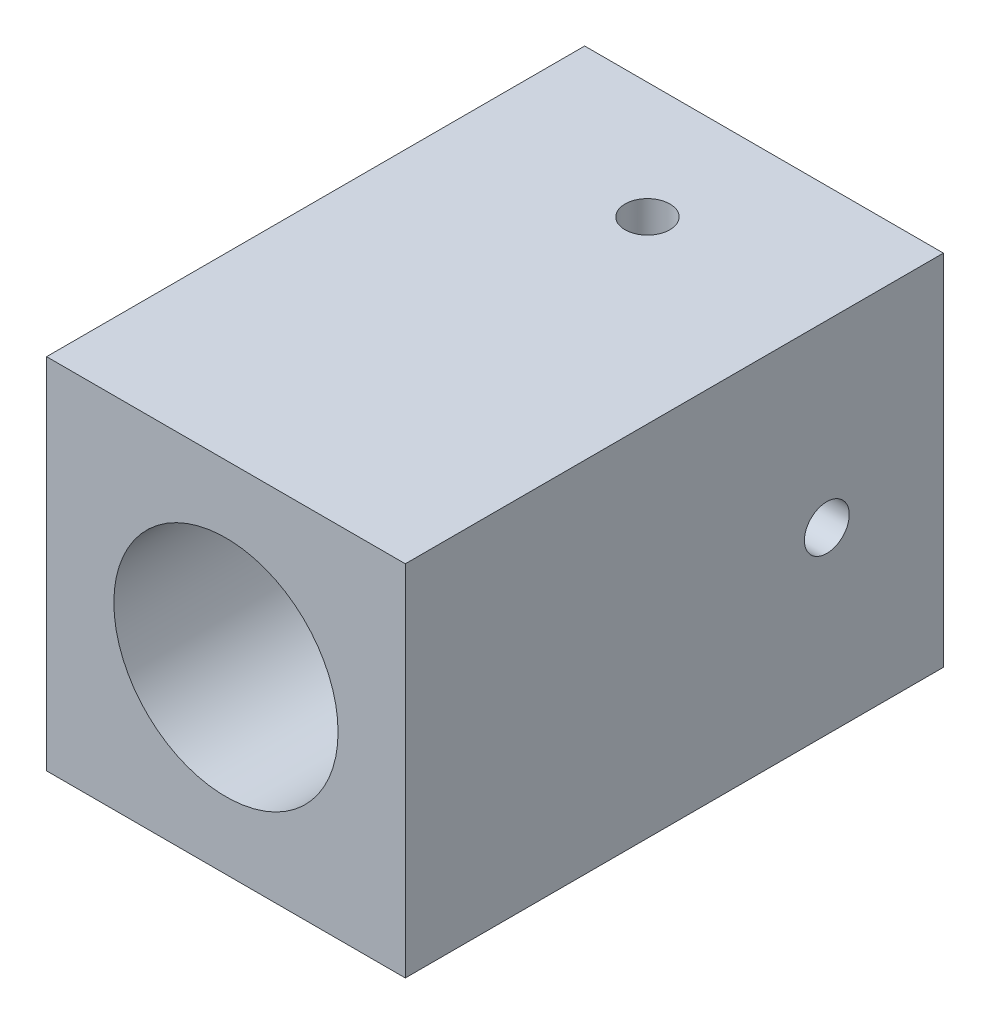
SolidWorks part; units mm, degrees
material "PETG-FDM"
ref_plane "前视基准面" through (0, 0, 0) normal (0, 0, 1) x (1, 0, 0)
ref_plane "上视基准面" through (0, 0, 0) normal (0, 1, 0) x (1, 0, 0)
ref_plane "右视基准面" through (0, 0, 0) normal (1, 0, 0) x (0, 0, -1)
other "Configuration Table"
sketch "草图1" plane through (0, 0, 0) normal (0, 0, 1) x (1, 0, 0)
  line L7 (-20, -20) -> (20, -20)
  line L8 (-20, -20) -> (-20, 20)
  line L9 (-20, 20) -> (20, 20)
  line L10 (20, -20) -> (20, 20)
  line L11 (-20, -20) -> (20, 20) construction
  line L12 (-20, 20) -> (20, -20) construction
  point P0 (0, 0)
  dimension "D1" = 40
  dimension "D2" = 40
extrude "凸台-拉伸1" add sketch "草图1" along normal blind 60
sketch "草图7" plane through (0, -20, 0) normal (0, -1, 0) x (1, 0, 0)
  line L0 (-20, 20) -> (20, 20) construction
  line L1 (-20, 60) -> (-20, 0) construction
  line L2 (20, 60) -> (20, 0) construction
  line L3 (-20, 0) -> (20, 0) construction
  line L4 (0, 0) -> (0, 20) construction
  circle A0 centre (0, 13) radius 2.5
  dimension "D2" = 5
  dimension "D1" = 20
  dimension "D3" = 7
extrude "切除-拉伸1" cut sketch "草图7" against normal blind 10
sketch "草图8" plane through (20, 0, 0) normal (1, 0, 0) x (0, 0, -1)
  line L0 (-20, 20) -> (-20, -20) construction
  line L1 (-60, 20) -> (0, 20) construction
  line L2 (-60, -20) -> (0, -20) construction
  line L3 (0, 0) -> (-20, 0) construction
  line L4 (0, -20) -> (0, 20) construction
  circle A0 centre (-13, 0) radius 2.5
  dimension "D2" = 5
  dimension "D1" = 20
  dimension "D3" = 7
extrude "切除-拉伸2" cut sketch "草图8" against normal blind 10
mirror "镜向1" about plane through (0, 0, 0) normal (0, 1, 0) of "切除-拉伸1"
mirror "镜向2" about plane through (0, 0, 0) normal (1, 0, 0) of "切除-拉伸2"
sketch "草图9" plane through (0, 0, 60) normal (0, 0, 1) x (1, 0, 0)
  circle A0 centre (0, 0) radius 28.2843
sketch "草图10" plane through (0, 0, 60) normal (0, 0, 1) x (1, 0, 0)
  circle A0 centre (0, 0) radius 12.5
  dimension "D1" = 25
extrude "切除-拉伸3" cut sketch "草图10" against normal blind 40
